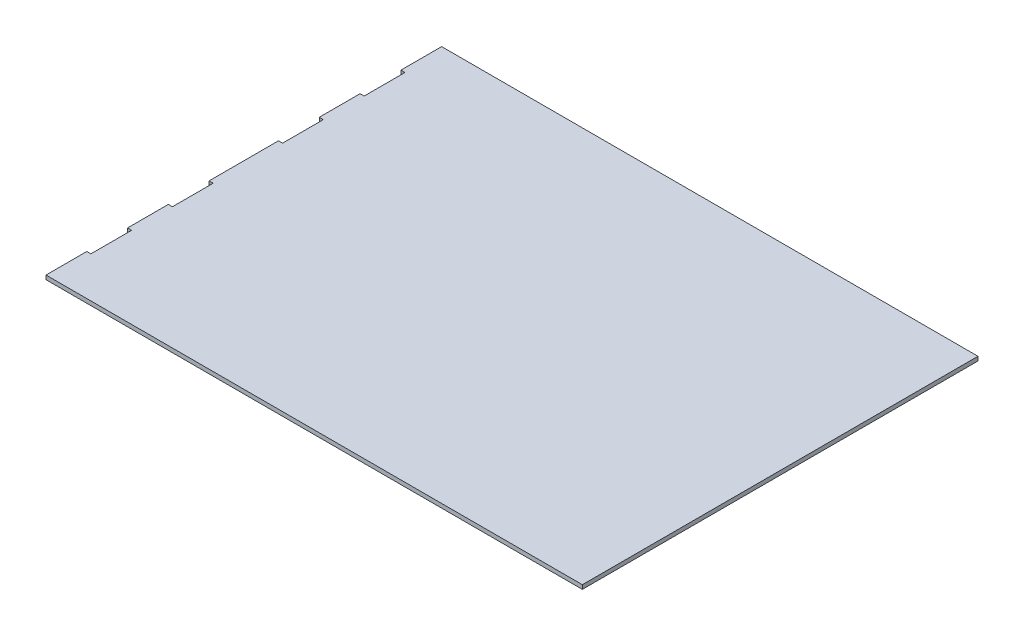
SolidWorks part; units mm, degrees
ref_plane "Front Plane" through (0, 0, 0) normal (0, 0, 1) x (1, 0, 0)
ref_plane "Top Plane" through (0, 0, 0) normal (0, 1, 0) x (1, 0, 0)
ref_plane "Right Plane" through (0, 0, 0) normal (1, 0, 0) x (0, 0, -1)
sketch "Sketch1" plane through (0, 0, 0) normal (0, 1, 0) x (1, 0, 0)
  line L4 (131.5, -97) -> (131.5, -77)
  line L5 (-131.5, -97) -> (131.5, 97) construction
  line L6 (-131.5, 97) -> (131.5, -97) construction
  line L26 (-55, 0) -> (55, 0) construction
  line L43 (0, -55) -> (0, 55) construction
  line L88 (-113.5, -97) -> (-103.5, -97)
  line L89 (-83.5, -97) -> (-73.5, -97)
  line L90 (-53.5, -97) -> (-43.5, -97)
  line L91 (73.5, -97) -> (83.5, -97)
  line L92 (-23.5, -97) -> (53.5, -97)
  line L93 (103.5, -97) -> (113.5, -97)
  line L95 (131.5, -57) -> (131.5, -37)
  line L96 (131.5, -17) -> (131.5, 17)
  line L97 (131.5, 37) -> (131.5, 57)
  line L98 (-131.5, 97) -> (-113.5, 97)
  line L99 (131.5, 77) -> (131.5, 97)
  line L101 (103.5, 97) -> (113.5, 97)
  line L102 (73.5, 97) -> (83.5, 97)
  line L103 (-23.5, 97) -> (53.5, 97)
  line L104 (-53.5, 97) -> (-43.5, 97)
  line L105 (-103.5, 97) -> (-83.5, 97)
  line L106 (-113.5, 97) -> (-103.5, 97)
  line L107 (-83.5, 97) -> (-73.5, 97)
  line L108 (-131.5, 97) -> (-131.5, -97)
  line L109 (-73.5, 97) -> (-53.5, 97)
  line L110 (-43.5, 97) -> (-23.5, 97)
  line L111 (53.5, 97) -> (73.5, 97)
  line L112 (83.5, 97) -> (103.5, 97)
  line L113 (113.5, 97) -> (131.5, 97)
  line L114 (131.5, 77) -> (131.5, 57)
  line L115 (131.5, 37) -> (131.5, 17)
  line L116 (131.5, -17) -> (131.5, -37)
  line L117 (131.5, -57) -> (131.5, -77)
  line L118 (131.5, -97) -> (113.5, -97)
  line L119 (103.5, -97) -> (83.5, -97)
  line L120 (73.5, -97) -> (53.5, -97)
  line L121 (-23.5, -97) -> (-43.5, -97)
  line L122 (-53.5, -97) -> (-73.5, -97)
  line L123 (-83.5, -97) -> (-103.5, -97)
  line L124 (-113.5, -97) -> (-131.5, -97)
  point P0 (0, 0)
  point P7 (0, 0)
  dimension "D1" = 263
  dimension "D2" = 194
extrude "Boss-Extrude1" add sketch "Sketch1" along normal blind 2
sketch "Sketch2" plane through (0, 2, 0) normal (0, 1, 0) x (1, 0, 0)
  line L0 (131.5, -97) -> (131.5, 97) construction
  line L1 (131.5, 77) -> (129.5, 77)
  line L2 (131.5, 77) -> (131.5, 57)
  line L3 (131.5, 57) -> (129.5, 57)
  line L4 (129.5, 77) -> (129.5, 57)
  line L5 (131.5, 97) -> (-131.5, 97) construction
  line L6 (131.5, 37) -> (129.5, 37)
  line L7 (131.5, 37) -> (131.5, 17)
  line L8 (131.5, 17) -> (129.5, 17)
  line L9 (129.5, 37) -> (129.5, 17)
  line L10 (-55, 0) -> (55, 0) construction
  line L11 (131.5, -17) -> (129.5, -17)
  line L12 (129.5, -37) -> (129.5, -17)
  line L13 (131.5, -37) -> (129.5, -37)
  line L14 (131.5, -37) -> (131.5, -17)
  line L15 (131.5, -57) -> (129.5, -57)
  line L16 (129.5, -77) -> (129.5, -57)
  line L17 (131.5, -77) -> (129.5, -77)
  line L18 (131.5, -77) -> (131.5, -57)
  dimension "D1" = 2
  dimension "D2" = 2
  dimension "D3" = 20
  dimension "D4" = 20
  dimension "D5" = 20
  dimension "D6" = 20
extrude "Cut-Extrude1" [suppressed] cut sketch "Sketch2" against normal blind 10
ref_plane "Plane1" through (-131.5, 2, -97) normal (0, 0, 1) x (1, 0, 0)
sketch "Sketch4" plane through (0, 2, 0) normal (0, 1, 0) x (1, 0, 0)
  line L0 (-131.5, 97) -> (-131.5, -97) construction
  line L1 (-131.5, 77) -> (-129.5, 77)
  line L2 (-131.5, 77) -> (-131.5, 57)
  line L3 (-131.5, 57) -> (-129.5, 57)
  line L4 (-129.5, 77) -> (-129.5, 57)
  line L5 (-137, 97) -> (-126, 97) construction
  line L6 (-131.5, 37) -> (-129.5, 37)
  line L7 (-131.5, 37) -> (-131.5, 17)
  line L8 (-131.5, 17) -> (-129.5, 17)
  line L9 (-129.5, 37) -> (-129.5, 17)
  line L10 (-55, 0) -> (55, 0) construction
  line L11 (-131.5, -17) -> (-129.5, -17)
  line L12 (-129.5, -37) -> (-129.5, -17)
  line L13 (-131.5, -37) -> (-129.5, -37)
  line L14 (-131.5, -37) -> (-131.5, -17)
  line L15 (-131.5, -57) -> (-129.5, -57)
  line L16 (-129.5, -77) -> (-129.5, -57)
  line L17 (-131.5, -77) -> (-129.5, -77)
  line L18 (-131.5, -77) -> (-131.5, -57)
  dimension "D1" = 2
  dimension "D2" = 20
  dimension "D3" = 2
  dimension "D4" = 20
  dimension "D5" = 20
  dimension "D6" = 20
extrude "Cut-Extrude2" cut sketch "Sketch4" against normal blind 10
